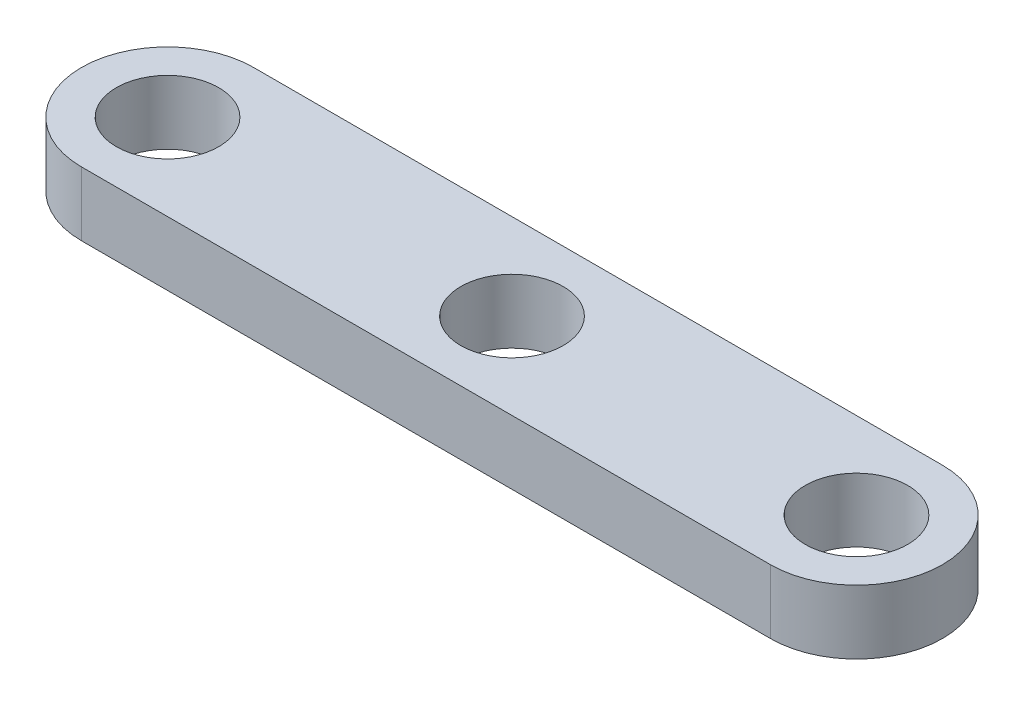
SolidWorks part; units mm, degrees
ref_plane "Front Plane" through (0, 0, 0) normal (0, 0, 1) x (1, 0, 0)
ref_plane "Top Plane" through (0, 0, 0) normal (0, 1, 0) x (1, 0, 0)
ref_plane "Right Plane" through (0, 0, 0) normal (1, 0, 0) x (0, 0, -1)
sketch "Sketch1" plane through (0, 0, 0) normal (0, 1, 0) x (1, 0, 0)
  line L1 (-20.18, 4.035) -> (20.18, 4.035)
  line L2 (-20.18, 4.035) -> (-20.18, -4.035)
  line L3 (-20.18, -4.035) -> (20.18, -4.035)
  line L4 (20.18, 4.035) -> (20.18, -4.035)
  line L5 (-20.18, 4.035) -> (20.18, -4.035) construction
  line L6 (-20.18, -4.035) -> (20.18, 4.035) construction
  circle A0 centre (-16.145, 0) radius 2.4
  circle A1 centre (16.145, 0) radius 2.4
  arc A2 (-16.145, 4.035) -> (-16.145, -4.035) centre (-16.145, 0) ccw
  arc A3 (16.145, -4.035) -> (16.145, 4.035) centre (16.145, 0) ccw
  circle A5 centre (0, 0) radius 2.4
  point P0 (0, 0)
  dimension "D3" = 4.8
  dimension "D4" = 4.8
  dimension "D9" = 4.8
  dimension "D1" = 40.36
  dimension "D2" = 8.07
  dimension "D5" = 4.035
  dimension "D6" = 4.035
  dimension "D7" = 4.035
  dimension "D8" = 4.035
extrude "Boss-Extrude2" add sketch "Sketch1" along normal blind 3 contours L3 A3 L1 A2 A5 A1 A0
equation "\"D6@Sketch1\"=\"D5@Sketch1\""
equation "\"D8@Sketch1\"=\"D7@Sketch1\""
